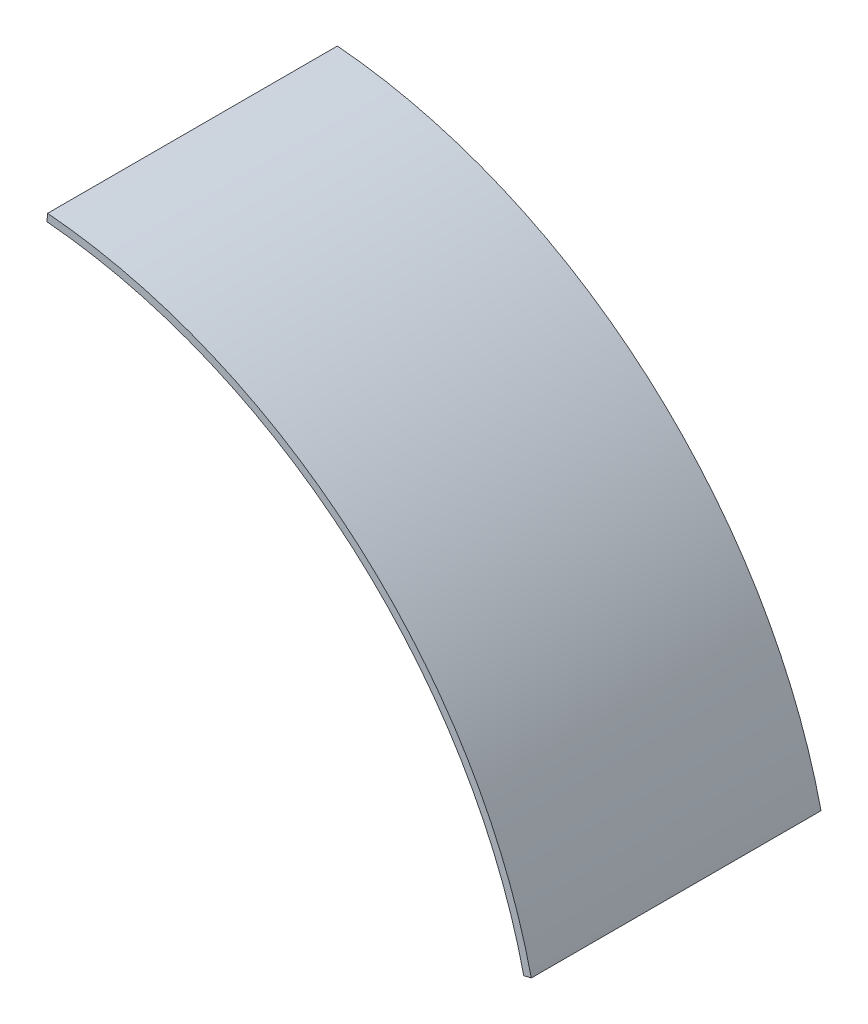
SolidWorks part; units mm, degrees
material "ABS PC"
ref_plane "前视基准面" through (0, 0, 0) normal (0, 0, 1) x (1, 0, 0)
ref_plane "上视基准面" through (0, 0, 0) normal (0, 1, 0) x (1, 0, 0)
ref_plane "右视基准面" through (0, 0, 0) normal (1, 0, 0) x (0, 0, -1)
sketch "草图1" plane through (0, 0, 0) normal (0, 0, 1) x (1, 0, 0)
  line L0 (0, 0) -> (61.054, 702.3513) construction
  line L1 (0, 0) -> (687.019, 158.2083) construction
  line L4 (0, 705) -> (0, 680)
  line L5 (673.3823, 94.6377) -> (698.139, 98.117)
  line L7 (61.054, 702.3513) -> (60.188, 692.3889)
  line L8 (687.019, 158.2083) -> (677.2741, 155.9642)
  arc A0 (698.139, 98.117) -> (0, 705) centre (0, 0) ccw construction
  arc A1 (60.188, 692.3889) -> (677.2741, 155.9642) centre (0, 0) cw
  arc A3 (698.139, 98.117) -> (0, 705) centre (0, 0) ccw
  arc A4 (673.3823, 94.6377) -> (0, 680) centre (0, 0) ccw
  arc A5 (687.019, 158.2083) -> (61.054, 702.3513) centre (0, 0) ccw
  dimension "D1" = 0
  dimension "D2" = 10
extrude "凸台-拉伸1" add sketch "草图1" against normal blind 375
